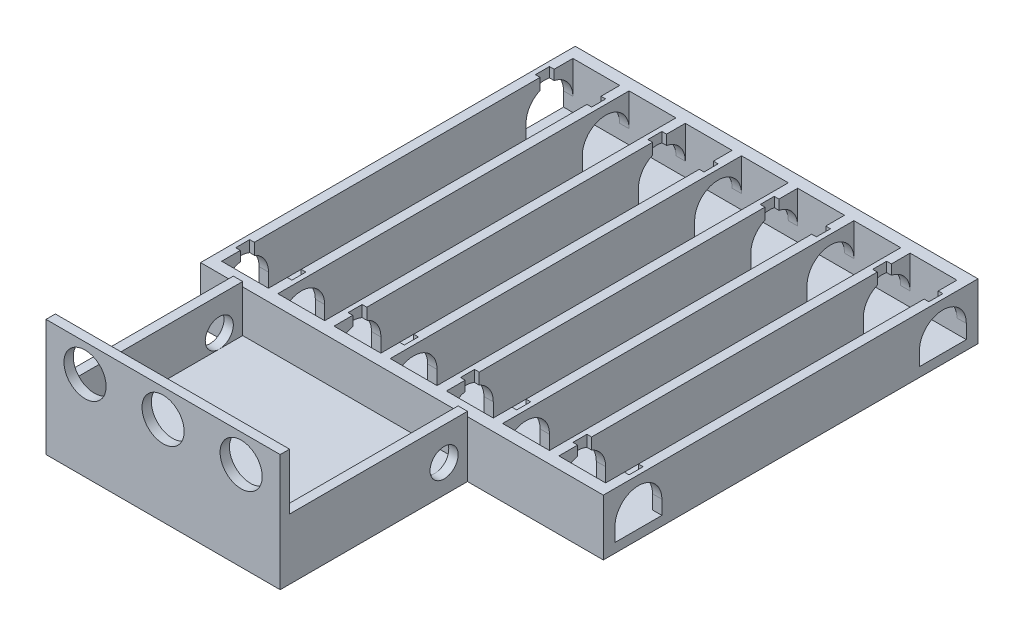
SolidWorks part; units mm, degrees
ref_plane "Front Plane" through (0, 0, 0) normal (0, 0, 1) x (1, 0, 0)
ref_plane "Top Plane" through (0, 0, 0) normal (0, 1, 0) x (1, 0, 0)
ref_plane "Right Plane" through (0, 0, 0) normal (1, 0, 0) x (0, 0, -1)
sketch "Sketch1" plane through (0, 0, 0) normal (0, 1, 0) x (1, 0, 0)
  line L1 (-7, -40) -> (7, -40)
  line L2 (-7, -40) -> (-7, 40)
  line L3 (-7, 40) -> (7, 40)
  line L4 (7, -40) -> (7, 40)
  line L5 (-7, -40) -> (7, 40) construction
  line L6 (-7, 40) -> (7, -40) construction
  point P0 (0, 0)
  dimension "D1" = 80
  dimension "D2" = 14
extrude "Boss-Extrude1" add sketch "Sketch1" along normal blind 2
sketch "Sketch2" plane through (0, 2, 0) normal (0, 1, 0) x (1, 0, 0)
  line L1 (-5, -37.5) -> (5, -37.5)
  line L2 (-5, -37.5) -> (-5, 37.5)
  line L3 (-5, 37.5) -> (5, 37.5)
  line L4 (5, -37.5) -> (5, 37.5)
  line L5 (-5, -37.5) -> (5, 37.5) construction
  line L6 (-5, 37.5) -> (5, -37.5) construction
  line L7 (7, -40) -> (-7, -40)
  line L8 (7, -40) -> (7, 40)
  line L9 (7, 40) -> (-7, 40)
  line L10 (-7, -40) -> (-7, 40)
  line L11 (7, -40) -> (-7, 40) construction
  line L12 (7, 40) -> (-7, -40) construction
  point P0 (0, 0)
  point P6 (0, 0)
  dimension "D1" = 75
  dimension "D2" = 10
extrude "Boss-Extrude2" add sketch "Sketch2" along normal blind 10
sketch "Sketch3" plane through (0, 12, 0) normal (0, 1, 0) x (1, 0, 0)
  line L0 (0, 0) -> (0, 37.5) construction
  line L1 (5, 37.5) -> (-5, 37.5) construction
  line L2 (0, 37.5) -> (5, 37.5) construction
  line L3 (5, 37.5) -> (5, 33.5) construction
  line L4 (-5, 37.5) -> (-5, 33.5) construction
  line L5 (0, 0) -> (0, -37.5) construction
  line L6 (-5, -37.5) -> (5, -37.5) construction
  line L7 (0, -37.5) -> (5, -37.5) construction
  line L8 (0, -37.5) -> (-5, -37.5) construction
  line L9 (-5, -37.5) -> (-5, -33.5) construction
  line L10 (5, -37.5) -> (5, -33.5) construction
  line L12 (-5, -33.5) -> (-6, -33.5)
  line L13 (-5, -33.5) -> (-5, -30.5)
  line L14 (-5, -30.5) -> (-6, -30.5)
  line L15 (-6, -33.5) -> (-6, -30.5)
  line L16 (5, -33.5) -> (6, -33.5)
  line L17 (5, -33.5) -> (5, -30.5)
  line L18 (5, -30.5) -> (6, -30.5)
  line L19 (6, -33.5) -> (6, -30.5)
  line L20 (5, 33.5) -> (6, 33.5)
  line L21 (5, 33.5) -> (5, 30.5)
  line L22 (5, 30.5) -> (6, 30.5)
  line L23 (6, 33.5) -> (6, 30.5)
  line L24 (-5, 33.5) -> (-6, 33.5)
  line L25 (-5, 33.5) -> (-5, 30.5)
  line L26 (-5, 30.5) -> (-6, 30.5)
  line L27 (-6, 33.5) -> (-6, 30.5)
  dimension "D1" = 4
  dimension "D2" = 1
  dimension "D3" = 3
extrude "Cut-Extrude1" cut sketch "Sketch3" against normal blind 10
sketch "Sketch4" plane through (7, 0, 0) normal (1, 0, 0) x (0, 0, -1)
  line L0 (0, 0) -> (0, 2) construction
  line L1 (-40, 0) -> (40, 0) construction
  line L2 (0, 2) -> (-32.5, 2) construction
  line L3 (-32.5, 2) -> (-32.5, 5) construction
  line L4 (0, 2) -> (32.5, 2) construction
  line L5 (32.5, 2) -> (32.5, 5) construction
  line L6 (32.5, 2) -> (37.5, 2)
  line L7 (37.5, 2) -> (37.5, 5)
  line L8 (-32.5, 2) -> (-37.5, 2)
  line L9 (-37.5, 2) -> (-37.5, 5)
  line L10 (-32.5, 2) -> (-27.5, 2)
  line L11 (32.5, 2) -> (27.5, 2)
  line L12 (-27.5, 2) -> (-27.5, 5)
  line L13 (27.5, 2) -> (27.5, 5)
  arc A0 (27.5, 5) -> (37.5, 5) centre (32.5, 5) cw
  arc A1 (-37.5, 5) -> (-27.5, 5) centre (-32.5, 5) cw
  dimension "D1" = 2
  dimension "D2" = 32.5
  dimension "D3" = 3
  dimension "D4" = 5
extrude "Cut-Extrude2" cut sketch "Sketch4" against normal blind 14 contours A1 L9 L8 L10 L12 | A0 L13 L11 L6 L7
sketch "Sketch5" plane through (0, 0, 0) normal (0, 1, 0) x (1, 0, 0)
  line L0 (0, 0) -> (7, 0) construction
  line L1 (7, -40) -> (7, 40) construction
  line L2 (7, 0) -> (7, -40) construction
  line L4 (7, -40) -> (79, -40)
  line L5 (7, -40) -> (7, 40)
  line L6 (7, 40) -> (79, 40)
  line L7 (79, -40) -> (79, 40)
  dimension "D1" = 72
  dimension "D2" = 80
extrude "Boss-Extrude3" add sketch "Sketch5" along normal blind 2
sketch "Sketch6" plane through (0, 2, 0) normal (0, 1, 0) x (1, 0, 0)
  line L0 (0, 0) -> (7, 0) construction
  line L1 (7, -40) -> (7, 40) construction
  line L2 (7, 0) -> (17, 0) construction
  line L3 (17, 0) -> (24, 0) construction
  line L4 (24, 0) -> (31, 0) construction
  line L5 (31, 0) -> (41, 0) construction
  line L6 (41, 0) -> (48, 0) construction
  line L7 (48, 0) -> (55, 0) construction
  line L8 (55, 0) -> (65, 0) construction
  line L9 (65, 0) -> (79, 0) construction
  line L10 (79, -40) -> (79, 40) construction
  line L11 (79, 40) -> (7, 40) construction
  line L12 (17, -40) -> (31, -40)
  line L13 (17, -40) -> (17, 40)
  line L14 (17, 40) -> (31, 40)
  line L15 (31, -40) -> (31, 40)
  line L16 (17, -40) -> (31, 40) construction
  line L17 (17, 40) -> (31, -40) construction
  line L18 (79, 0) -> (79, -40) construction
  line L19 (41, -40) -> (55, -40)
  line L20 (41, -40) -> (41, 40)
  line L21 (41, 40) -> (55, 40)
  line L22 (55, -40) -> (55, 40)
  line L23 (41, -40) -> (55, 40) construction
  line L24 (41, 40) -> (55, -40) construction
  line L26 (79, -40) -> (65, -40)
  line L27 (79, -40) -> (79, 40)
  line L28 (79, 40) -> (65, 40)
  line L29 (65, -40) -> (65, 40)
  line L30 (19, -37.5) -> (29, -37.5)
  line L31 (19, -37.5) -> (19, 37.5)
  line L32 (19, 37.5) -> (29, 37.5)
  line L33 (29, -37.5) -> (29, 37.5)
  line L34 (19, -37.5) -> (29, 37.5) construction
  line L35 (19, 37.5) -> (29, -37.5) construction
  line L36 (43, -37.5) -> (53, -37.5)
  line L37 (43, -37.5) -> (43, 37.5)
  line L38 (43, 37.5) -> (53, 37.5)
  line L39 (53, -37.5) -> (53, 37.5)
  line L40 (43, -37.5) -> (53, 37.5) construction
  line L41 (43, 37.5) -> (53, -37.5) construction
  line L42 (67, -37.5) -> (77, -37.5)
  line L43 (67, -37.5) -> (67, 37.5)
  line L44 (67, 37.5) -> (77, 37.5)
  line L45 (77, -37.5) -> (77, 37.5)
  line L46 (67, -37.5) -> (77, 37.5) construction
  line L47 (67, 37.5) -> (77, -37.5) construction
  point P38 (72, 0)
  dimension "D1" = 7
  dimension "D2" = 10
  dimension "D3" = 14
  dimension "D4" = 10
  dimension "D5" = 75
extrude "Boss-Extrude4" add sketch "Sketch6" along normal blind 10
ref_plane "Plane1" through (12, 0, 0) normal (-1, 0, 0) x (0, 0, 1)
mirror "Mirror1" about plane through (12, 0, 0) normal (-1, 0, 0) of "Cut-Extrude1"
ref_plane "Plane2" through (36, 0, 0) normal (-1, 0, 0) x (0, 0, 1)
mirror "Mirror2" about plane through (36, 0, 0) normal (-1, 0, 0) of "Mirror1", "Cut-Extrude1"
mirror "Mirror4" about plane through (12, 0, 0) normal (-1, 0, 0) of "Cut-Extrude2"
mirror "Mirror5" about plane through (36, 0, 0) normal (-1, 0, 0) of "Mirror4", "Cut-Extrude2"
sketch "Sketch7" plane through (0, 2, 0) normal (0, 1, 0) x (1, 0, 0)
  line L0 (31, -40) -> (31, 40) construction
  line L1 (7, 40) -> (17, 40)
  line L2 (7, 40) -> (7, 37.5)
  line L3 (7, 37.5) -> (17, 37.5)
  line L4 (17, 40) -> (17, 37.5)
  line L5 (31, 40) -> (41, 40)
  line L6 (31, 40) -> (31, 37.5)
  line L7 (31, 37.5) -> (41, 37.5)
  line L8 (41, 40) -> (41, 37.5)
  line L9 (55, 40) -> (65, 40)
  line L10 (55, 40) -> (55, 37.5)
  line L11 (55, 37.5) -> (65, 37.5)
  line L12 (65, 40) -> (65, 37.5)
  line L13 (65, -40) -> (55, -40)
  line L14 (65, -40) -> (65, -37.5)
  line L15 (65, -37.5) -> (55, -37.5)
  line L16 (55, -40) -> (55, -37.5)
  line L17 (41, -40) -> (31, -40)
  line L18 (41, -40) -> (41, -37.5)
  line L19 (41, -37.5) -> (31, -37.5)
  line L20 (31, -40) -> (31, -37.5)
  line L22 (17, -40) -> (7, -40)
  line L23 (17, -40) -> (17, -37.5)
  line L24 (17, -37.5) -> (7, -37.5)
  line L25 (7, -40) -> (7, -37.5)
extrude "Boss-Extrude5" add sketch "Sketch7" along normal blind 10
sketch "Sketch8" plane through (0, 0, 0) normal (0, 1, 0) x (1, 0, 0)
  line L0 (0, 0) -> (0, -40) construction
  line L1 (-7, -40) -> (79, -40) construction
  line L3 (0, -40) -> (50, -40)
  line L4 (0, -40) -> (0, -80)
  line L5 (0, -80) -> (50, -80)
  line L6 (50, -40) -> (50, -80)
  dimension "D1" = 40
  dimension "D2" = 50
extrude "Boss-Extrude6" add sketch "Sketch8" along normal blind 3
sketch "Sketch9" plane through (0, 3, 0) normal (0, 1, 0) x (1, 0, 0)
  line L0 (0, -40) -> (0, -80)
  line L1 (0, -80) -> (50, -80)
  line L2 (50, -80) -> (50, -40)
  line L3 (50, -40) -> (48, -40)
  line L4 (50, -40) -> (0, -40) construction
  line L5 (48, -40) -> (48, -78)
  line L6 (48, -78) -> (2, -78)
  line L7 (2, -78) -> (2, -40)
  line L8 (2, -40) -> (0, -40)
  dimension "D1" = 2
  dimension "D2" = 2
  dimension "D3" = 2
extrude "Boss-Extrude7" add sketch "Sketch9" along normal blind 10
sketch "Sketch10" plane through (0, 0, 0) normal (-1, 0, 0) x (0, 0, 1)
  line L0 (60, 0) -> (60, 2) construction
  line L1 (40, 0) -> (80, 0) construction
  line L2 (60, 2) -> (45, 2) construction
  line L3 (45, 2) -> (45, 6) construction
  circle A0 centre (45, 6) radius 3
  dimension "D4" = 6
  dimension "D1" = 2
  dimension "D2" = 15
  dimension "D3" = 4
extrude "Cut-Extrude3" cut sketch "Sketch10" against normal blind 50
sketch "Sketch11" plane through (0, 13, 0) normal (0, 1, 0) x (1, 0, 0)
  line L0 (50, -80) -> (50, -40) construction
  line L1 (0, -80) -> (50, -80)
  line L2 (0, -80) -> (0, -78)
  line L3 (0, -78) -> (50, -78)
  line L4 (50, -80) -> (50, -78)
  dimension "D1" = 2
extrude "Boss-Extrude8" add sketch "Sketch11" along normal blind 12
sketch "Sketch12" plane through (0, 0, 80) normal (0, 0, 1) x (1, 0, 0)
  line L0 (0, 25) -> (16.6667, 25) construction
  line L1 (16.6667, 25) -> (33.3333, 25) construction
  line L2 (33.3333, 25) -> (50, 25) construction
  line L3 (8.3333, 25) -> (8.3333, 19) construction
  line L4 (25, 25) -> (25, 19) construction
  line L5 (41.6667, 25) -> (41.6667, 19) construction
  circle A0 centre (8.3333, 19) radius 4.5
  circle A1 centre (25, 19) radius 4.5
  circle A2 centre (41.6667, 19) radius 4.5
  dimension "D4" = 9
  dimension "D1" = 16.6667
  dimension "D2" = 16.6667
  dimension "D3" = 6
extrude "Cut-Extrude4" cut sketch "Sketch12" against normal blind 2
